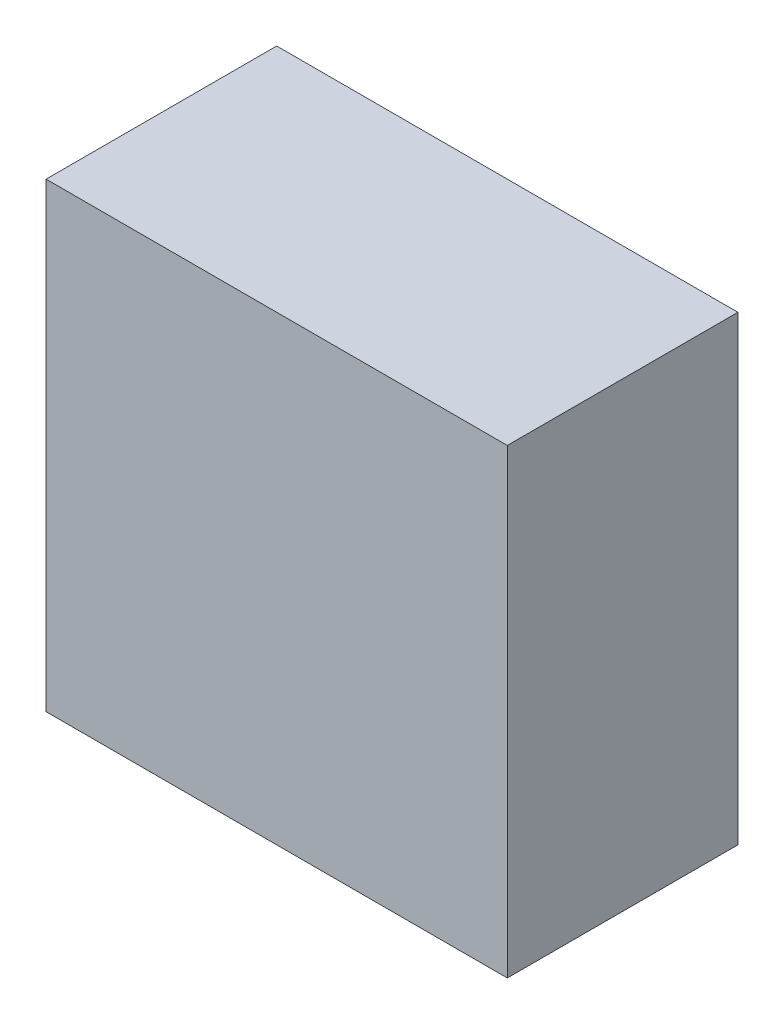
SolidWorks part; units mm, degrees
ref_plane "前视基准面" through (0, 0, 0) normal (0, 0, 1) x (1, 0, 0)
ref_plane "上视基准面" through (0, 0, 0) normal (0, 1, 0) x (1, 0, 0)
ref_plane "右视基准面" through (0, 0, 0) normal (1, 0, 0) x (0, 0, -1)
other "Configuration Table"
sketch "草图1" plane through (0, 0, 0) normal (0, 0, 1) x (1, 0, 0)
  line L1 (0, 0) -> (40000, 0)
  line L2 (0, 0) -> (0, 40000)
  line L3 (0, 40000) -> (40000, 40000)
  line L4 (40000, 0) -> (40000, 40000)
extrude "凸台-拉伸1" add sketch "草图1" against normal blind 20000
